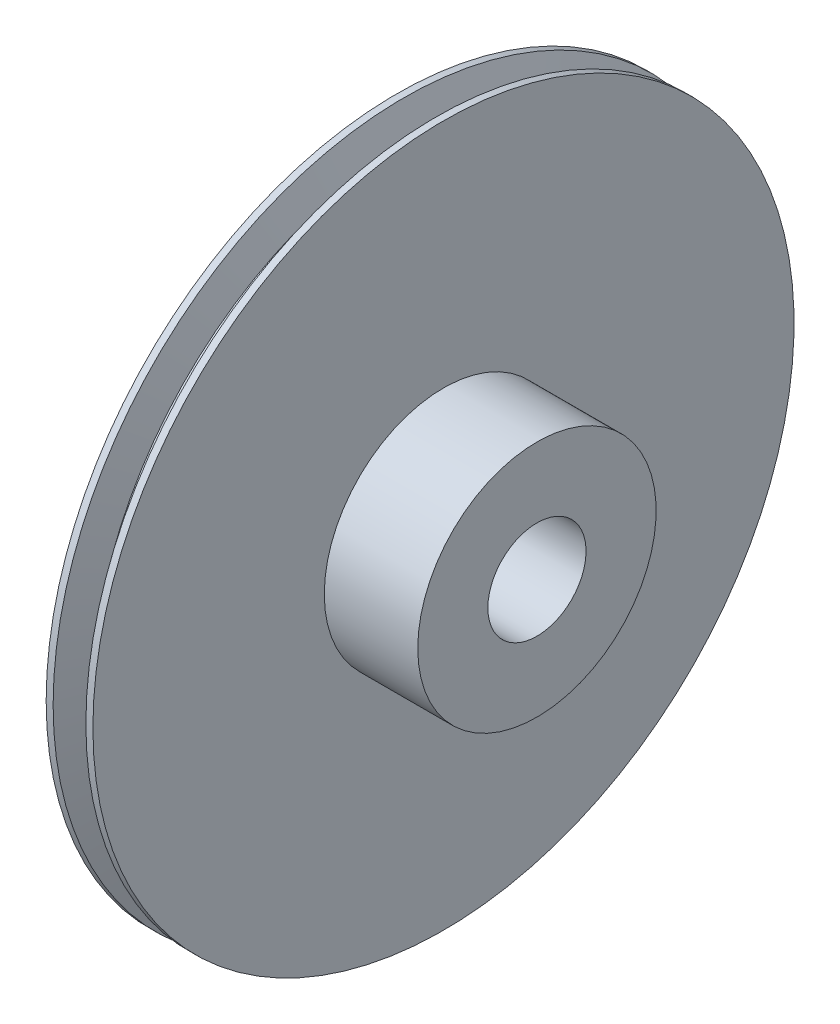
SolidWorks part; units mm, degrees
ref_plane "Front Plane" through (0, 0, 0) normal (0, 0, 1) x (1, 0, 0)
ref_plane "Top Plane" through (0, 0, 0) normal (0, 1, 0) x (1, 0, 0)
ref_plane "Right Plane" through (0, 0, 0) normal (1, 0, 0) x (0, 0, -1)
sketch "Sketch1" plane through (0, 0, 0) normal (0, 0, 1) x (1, 0, 0)
  line L0 (0, 0) -> (120.6523, 0) construction
  line L1 (0, 10.5) -> (0, 75)
  line L7 (10, 75) -> (10, 25.5)
  line L8 (10, 25.5) -> (30, 25.5)
  line L9 (30, 25.5) -> (30, 10.5)
  line L10 (30, 10.5) -> (0, 10.5)
  line L11 (0, 75) -> (1.4895, 75)
  line L12 (5, 68.9272) -> (5, 10.5) construction
  line L13 (3.8197, 68.9272) -> (6.1803, 68.9272)
  line L14 (6.1803, 68.9272) -> (8.496, 75)
  line L15 (3.8197, 68.9272) -> (1.4895, 75)
  line L16 (8.496, 75) -> (10, 75)
  point P5 (0, 0)
  point P15 (5, 68.9272)
  dimension "D1" = 10.5
  dimension "D2" = 75
  dimension "D3" = 30
  dimension "D4" = 20
  dimension "D5" = 2.3605
  dimension "D6" = 1.4895
  dimension "D7" = 1.504
  dimension "D8" = 6.0728
  dimension "D9" = 5
  dimension "D10" = 15
revolve "Revolve1" add sketch "Sketch1" angle 360 about L0
